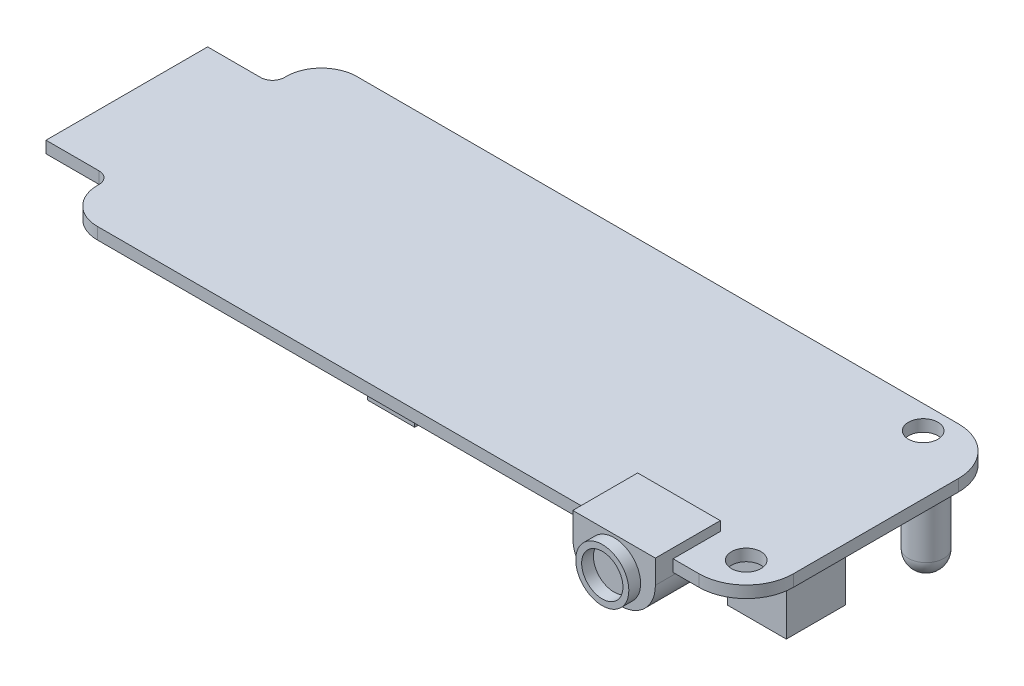
SolidWorks part; units mm, degrees
ref_plane "Спереди" through (0, 0, 0) normal (0, 0, 1) x (1, 0, 0)
ref_plane "Сверху" through (0, 0, 0) normal (0, 1, 0) x (1, 0, 0)
ref_plane "Справа" through (0, 0, 0) normal (1, 0, 0) x (0, 0, -1)
sketch "Эскиз1" plane through (0, 0, 0) normal (0, 1, 0) x (1, 0, 0)
  line L0 (58, 11) -> (-2.75, 11) construction
  line L1 (3, 0) -> (54, 0)
  line L2 (0, 3) -> (0, 3.15)
  line L3 (3, 22) -> (54, 22)
  line L4 (58, 4) -> (58, 18)
  line L5 (0, 18.85) -> (0, 19)
  line L6 (-5.5, 17.85) -> (-1, 17.85)
  line L7 (-5.5, 17.85) -> (-5.5, 4.15)
  line L8 (-5.5, 4.15) -> (-1, 4.15)
  line L10 (-5.5, 17.85) -> (0, 4.15) construction
  line L11 (-5.5, 4.15) -> (0, 17.85) construction
  circle A0 centre (53, 20) radius 1.25
  circle A1 centre (55, 3) radius 1.25
  arc A2 (54, 0) -> (58, 4) centre (54, 4) ccw
  arc A3 (58, 18) -> (54, 22) centre (54, 18) ccw
  arc A4 (3, 0) -> (0, 3) centre (3, 3) cw
  arc A5 (0, 19) -> (3, 22) centre (3, 19) cw
  arc A6 (0, 3.15) -> (-1, 4.15) centre (-1, 3.15) ccw
  arc A7 (0, 18.85) -> (-1, 17.85) centre (-1, 18.85) cw
  point P13 (58, 22)
  point P16 (0, 0)
  point P19 (0, 22)
  dimension "D3" = 2.5
  dimension "D8" = 4
  dimension "D9" = 3
  dimension "D12" = 1
  dimension "D1" = 22
  dimension "D2" = 58
  dimension "D4" = 3
  dimension "D5" = 3
  dimension "D6" = 5
  dimension "D7" = 2
  dimension "D10" = 63.5
  dimension "D11" = 13.7
extrude "Бобышка-Вытянуть1" add sketch "Эскиз1" along normal blind 1
sketch "Эскиз2" plane through (0, 0, 0) normal (0, -1, 0) x (1, 0, 0)
  line L0 (58, -4) -> (58, -18) construction
  line L1 (54, -22) -> (3, -22) construction
  circle A0 centre (55.75, -17.5) radius 1.5
  circle A1 centre (55.75, -17.5) radius 2.25 construction
  dimension "D1" = 3
  dimension "D2" = 4.5
  dimension "D3" = 4.5
extrude "Бобышка-Вытянуть2" add sketch "Эскиз2" along normal blind 6.5
fillet "Скругление1" radius 1.5 1 edges at (55.75, -6.5, -19)
sketch "Эскиз3" plane through (0, 0, 0) normal (0, -1, 0) x (1, 0, 0)
  line L0 (54, -22) -> (3, -22) construction
  line L1 (58, -4) -> (58, -18) construction
  circle A0 centre (7.5, -12) radius 3.25
  circle A1 centre (26, -16.5) radius 3.25
  dimension "D1" = 6.5
  dimension "D2" = 5.5
  dimension "D3" = 32
  dimension "D4" = 50.5
  dimension "D5" = 10
extrude "Бобышка-Вытянуть3" add sketch "Эскиз3" along normal blind 6
fillet "Скругление2" radius 0.5 2 edges at (26, -6, -19.75) (7.5, -6, -15.25)
sketch "Эскиз4" plane through (0, 0, 0) normal (0, -1, 0) x (1, 0, 0)
  line L0 (58, -4) -> (58, -18) construction
  line L1 (56.3, -5.1) -> (51.3, -5.1)
  line L2 (56.3, -5.1) -> (56.3, -10.1)
  line L3 (56.3, -10.1) -> (51.3, -10.1)
  line L4 (51.3, -5.1) -> (51.3, -10.1)
  line L5 (3, 0) -> (54, 0) construction
  dimension "D1" = 5
  dimension "D2" = 1.7
  dimension "D3" = 5.1
extrude "Бобышка-Вытянуть4" add sketch "Эскиз4" along normal blind 5.2
sketch "Эскиз5" plane through (0, 0, 0) normal (0, -1, 0) x (1, 0, 0)
  line L0 (54, -22) -> (3, -22) construction
  line L1 (38, -10.7) -> (42, -10.7)
  line L2 (38, -10.7) -> (38, -14.7)
  line L3 (38, -14.7) -> (42, -14.7)
  line L4 (42, -10.7) -> (42, -14.7)
  line L5 (15.5, -8.6) -> (21, -8.6)
  line L6 (15.5, -8.6) -> (15.5, -14.1)
  line L7 (15.5, -14.1) -> (21, -14.1)
  line L8 (21, -8.6) -> (21, -14.1)
  line L13 (28.6, -10.2) -> (33.6, -10.2)
  line L14 (28.6, -10.2) -> (28.6, -13.5)
  line L15 (28.6, -13.5) -> (33.6, -13.5)
  line L16 (33.6, -10.2) -> (33.6, -13.5)
  line L17 (58, -4) -> (58, -18) construction
  dimension "D1" = 4
  dimension "D2" = 5
  dimension "D3" = 3.3
  dimension "D4" = 5.5
  dimension "D5" = 7.9
  dimension "D6" = 42.5
  dimension "D7" = 29.4
  dimension "D8" = 20
  dimension "D9" = 11.3
  dimension "D10" = 11.8
extrude "Бобышка-Вытянуть5" add sketch "Эскиз5" along normal blind 1
sketch "Эскиз6" plane through (0, 0, 0) normal (0, -1, 0) x (1, 0, 0)
  line L0 (3, 0) -> (54, 0) construction
  line L1 (23.5, -6.8) -> (27, -6.8)
  line L2 (23.5, -6.8) -> (23.5, -9.6)
  line L3 (23.5, -9.6) -> (27, -9.6)
  line L4 (27, -6.8) -> (27, -9.6)
  line L5 (58, -4) -> (58, -18) construction
  dimension "D1" = 3.5
  dimension "D2" = 2.8
  dimension "D3" = 6.8
  dimension "D4" = 34.5
extrude "Бобышка-Вытянуть6" add sketch "Эскиз6" along normal blind 2.2
fillet "Скругление3" radius 1 4 edges at (27, -1.1, -6.8) (27, -1.1, -9.6) (23.5, -1.1, -6.8) (23.5, -1.1, -9.6)
sketch "Эскиз7" plane through (0, 0, 0) normal (0, -1, 0) x (1, 0, 0)
  line L1 (44.8, -4) -> (51.8, -4)
  line L2 (44.8, -4) -> (44.8, 2.5)
  line L3 (44.8, 2.5) -> (51.8, 2.5)
  line L4 (51.8, -4) -> (51.8, 2.5)
  line L5 (3, 0) -> (54, 0) construction
  line L6 (58, -4) -> (58, -18) construction
  dimension "D1" = 7
  dimension "D2" = 4
  dimension "D3" = 6.5
  dimension "D4" = 6.2
extrude "Бобышка-Вытянуть7" add sketch "Эскиз7" along normal blind 5 from offset 1.8 offset against normal yes
fillet "Скругление4" radius 3 2 edges at (51.8, -3.2, -0.75) (44.8, -3.2, -0.75)
sketch "Эскиз8" plane through (0, 0, 2.5) normal (0, 0, 1) x (1, 0, 0)
  line L0 (48.3, -3.2) -> (48.3, -0.7) construction
  line L1 (48.8, -3.2) -> (47.8, -3.2) construction
  line L2 (48.3, -0.7) -> (48.3, 1.8) construction
  line L3 (51.8, 1.8) -> (44.8, 1.8) construction
  circle A0 centre (48.3, -0.7) radius 2.25
  circle A1 centre (48.3, -0.7) radius 6.7785
  circle A2 centre (48.3, -0.7) radius 1.75
  line M3 (47.8, -3.2) -> (48.8, -3.2)
  arc M4 (48.8, -3.2) -> (51.8, -0.2) centre (48.8, -0.2) ccw
  line M5 (51.8, -0.2) -> (51.8, 1.8)
  line M6 (51.8, 1.8) -> (44.8, 1.8)
  line M7 (44.8, 1.8) -> (44.8, -0.2)
  arc M8 (44.8, -0.2) -> (47.8, -3.2) centre (47.8, -0.2) ccw
  dimension "D1" = 4.5
  dimension "D2" = 0.5
extrude "Вырез-Вытянуть1" cut sketch "Эскиз8" against normal blind 1 contours A0 M8 M3 M4 M5 M6 M7 | A2
sketch "Эскиз9" plane through (0, 0, 0) normal (0, -1, 0) x (1, 0, 0)
  line L0 (3, 0) -> (44.8, 0) construction
  line L1 (4.5, -1.5) -> (8, -1.5)
  line L2 (4.5, -1.5) -> (4.5, -7.5)
  line L3 (4.5, -7.5) -> (8, -7.5)
  line L4 (8, -1.5) -> (8, -7.5)
  line L5 (58, -4) -> (58, -18) construction
  line L7 (24.7, -1.2) -> (28.7, -1.2)
  line L8 (24.7, -1.2) -> (24.7, -6.3)
  line L9 (24.7, -6.3) -> (28.7, -6.3)
  line L10 (28.7, -1.2) -> (28.7, -6.3)
  dimension "D1" = 3.5
  dimension "D2" = 6
  dimension "D3" = 1.5
  dimension "D4" = 53.5
  dimension "D5" = 4
  dimension "D6" = 5.1
  dimension "D7" = 1.2
  dimension "D8" = 33.3
extrude "Бобышка-Вытянуть8" add sketch "Эскиз9" along normal blind 1.5
